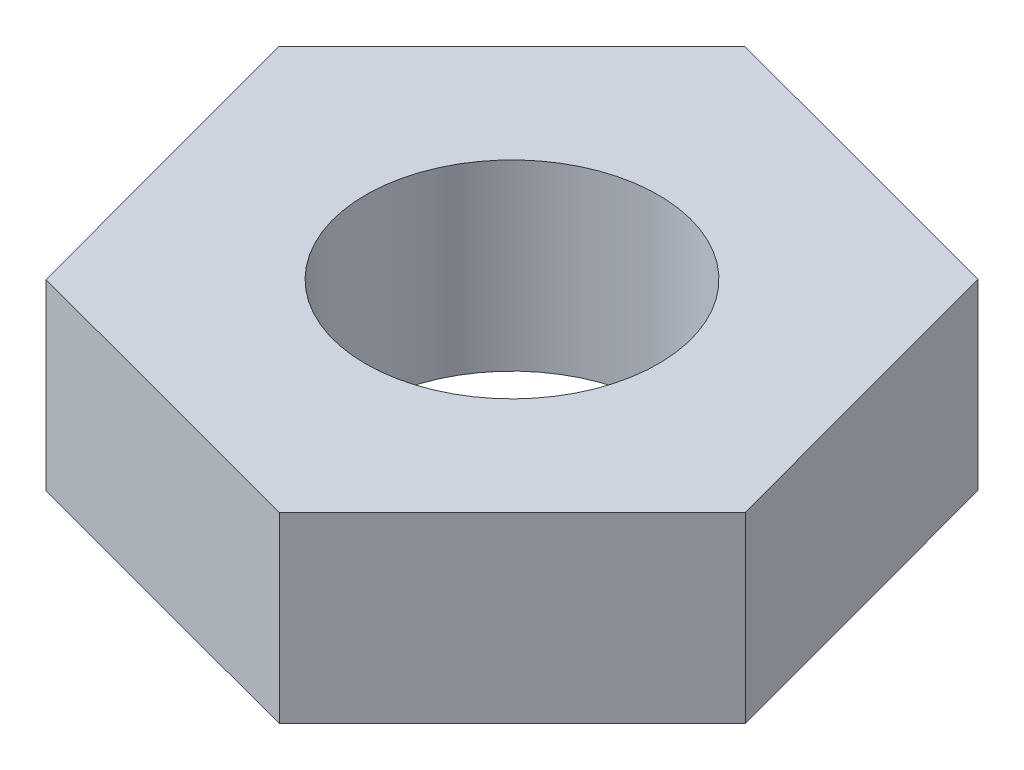
SolidWorks part; units mm, degrees
ref_plane "Plan de face" through (0, 0, 0) normal (0, 0, 1) x (1, 0, 0)
ref_plane "Plan de dessus" through (0, 0, 0) normal (0, 1, 0) x (1, 0, 0)
ref_plane "Plan de droite" through (0, 0, 0) normal (1, 0, 0) x (0, 0, -1)
sketch "Esquisse1" plane through (0, 0, 0) normal (0, 1, 0) x (1, 0, 0)
  line L1 (-4.3508, 1.1623) -> (-3.1819, -3.1867)
  line L2 (-3.1819, -3.1867) -> (1.1688, -4.349)
  line L3 (1.1688, -4.349) -> (4.3508, -1.1623)
  line L4 (4.3508, -1.1623) -> (3.1819, 3.1867)
  line L5 (3.1819, 3.1867) -> (-1.1688, 4.349)
  line L6 (-1.1688, 4.349) -> (-4.3508, 1.1623)
  circle A0 centre (0, 0) radius 3.9 construction
  circle A1 centre (0, 0) radius 2
  dimension "D2" = 4
  dimension "D1" = 7.8
extrude "Boss.-Extru.1" add sketch "Esquisse1" along normal blind 2.5
sketch "Esquisse7" plane through (0, 0, 0) normal (0, -1, 0) x (1, 0, 0)
  circle A0 centre (0, 0) radius 2
